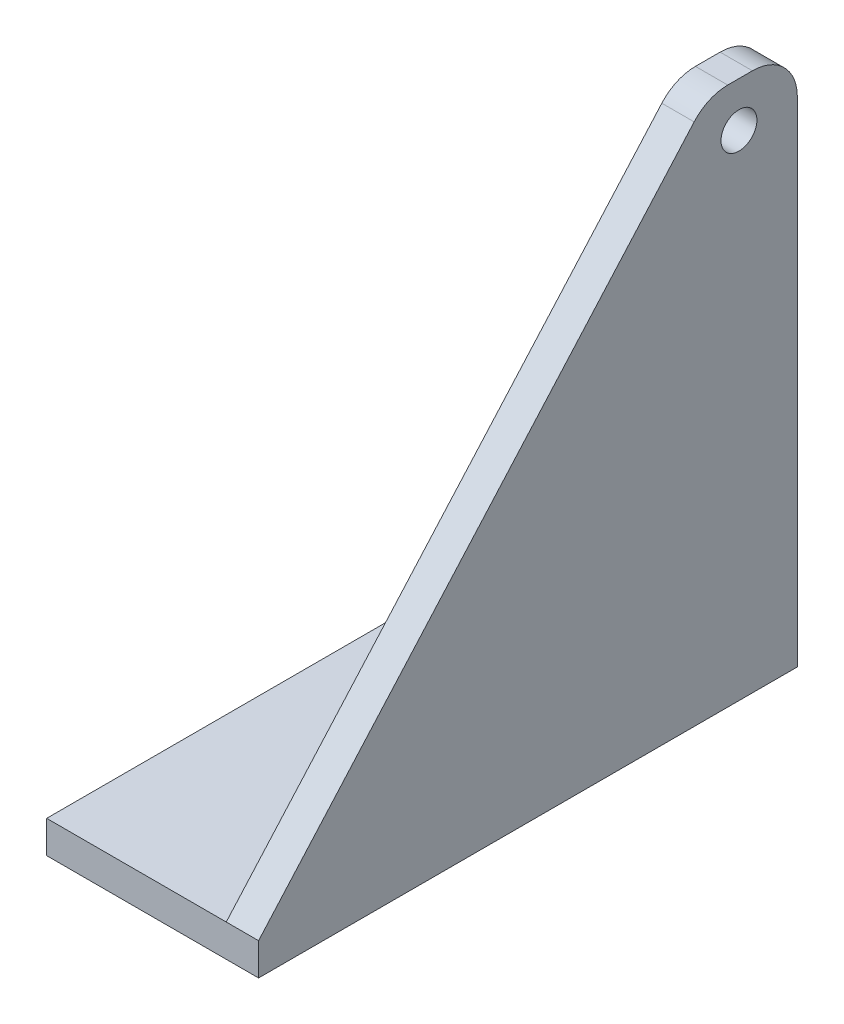
SolidWorks part; units mm, degrees
material "6061 Alloy"
ref_plane "Front Plane" through (0, 0, 0) normal (0, 0, 1) x (1, 0, 0)
ref_plane "Top Plane" through (0, 0, 0) normal (0, 1, 0) x (1, 0, 0)
ref_plane "Right Plane" through (0, 0, 0) normal (1, 0, 0) x (0, 0, -1)
sketch "Sketch1" plane through (0, 0, 0) normal (0, 0, 1) x (1, 0, 0)
  line L7 (0, 0) -> (25.4, 0)
  line L8 (0, 0) -> (0, 4.572)
  line L9 (0, 4.572) -> (25.4, 4.572)
  line L10 (25.4, 0) -> (25.4, 4.572)
  point P5 (0, 2.286)
  dimension "D1" = 4.572
  dimension "D2" = 25.4
extrude "Boss-Extrude1" add sketch "Sketch1" along normal blind 76.2
sketch "Sketch2" plane through (0, 0, 0) normal (-1, 0, 0) x (0, 0, 1)
  line L0 (12.7, 76.2) -> (76.2, 4.572)
  line L1 (76.2, 0) -> (0, 0) construction
  line L3 (0, 0) -> (0, 76.2)
  line L4 (76.2, 0) -> (0, 0)
  line L7 (76.2, 0) -> (76.2, 4.572) construction
  line L8 (76.2, 0) -> (76.2, 4.572)
  line L9 (0, 76.2) -> (12.7, 76.2)
  dimension "D1" = 76.2
  dimension "D2" = 12.7
sketch "Sketch4" plane through (25.4, 0, 0) normal (1, 0, 0) x (0, 0, -1)
  line L0 (-76.2, 0) -> (-76.2, 4.572) construction
  line L1 (-76.2, 0) -> (0, 0) construction
  line L2 (0, 0) -> (0, 76.2) construction
  line L3 (0, 76.2) -> (-12.7, 76.2) construction
  line L4 (-12.7, 76.2) -> (-76.2, 4.572) construction
  line L5 (-76.2, 0) -> (-76.2, 4.572)
  line L6 (-76.2, 0) -> (0, 0)
  line L7 (0, 0) -> (0, 76.2)
  line L8 (0, 76.2) -> (-12.7, 76.2)
  line L9 (-12.7, 76.2) -> (-76.2, 4.572)
extrude "Boss-Extrude3" add sketch "Sketch4" along normal blind 4.572
fillet "Fillet3" radius 6.35 2 edges at (27.686, 76.2, 0) (27.686, 76.2, 12.7)
sketch "Sketch5" plane through (29.972, 0, 0) normal (1, 0, 0) x (0, 0, -1)
  line L0 (0, 0) -> (0, 76.2) construction
  line L1 (-76.2, 0) -> (0, 0) construction
  circle A0 centre (-8.255, 69.85) radius 2.54
  dimension "D1" = 5.08
  dimension "D2" = 8.255
  dimension "D3" = 69.85
extrude "Cut-Extrude2" cut sketch "Sketch5" against normal through all
